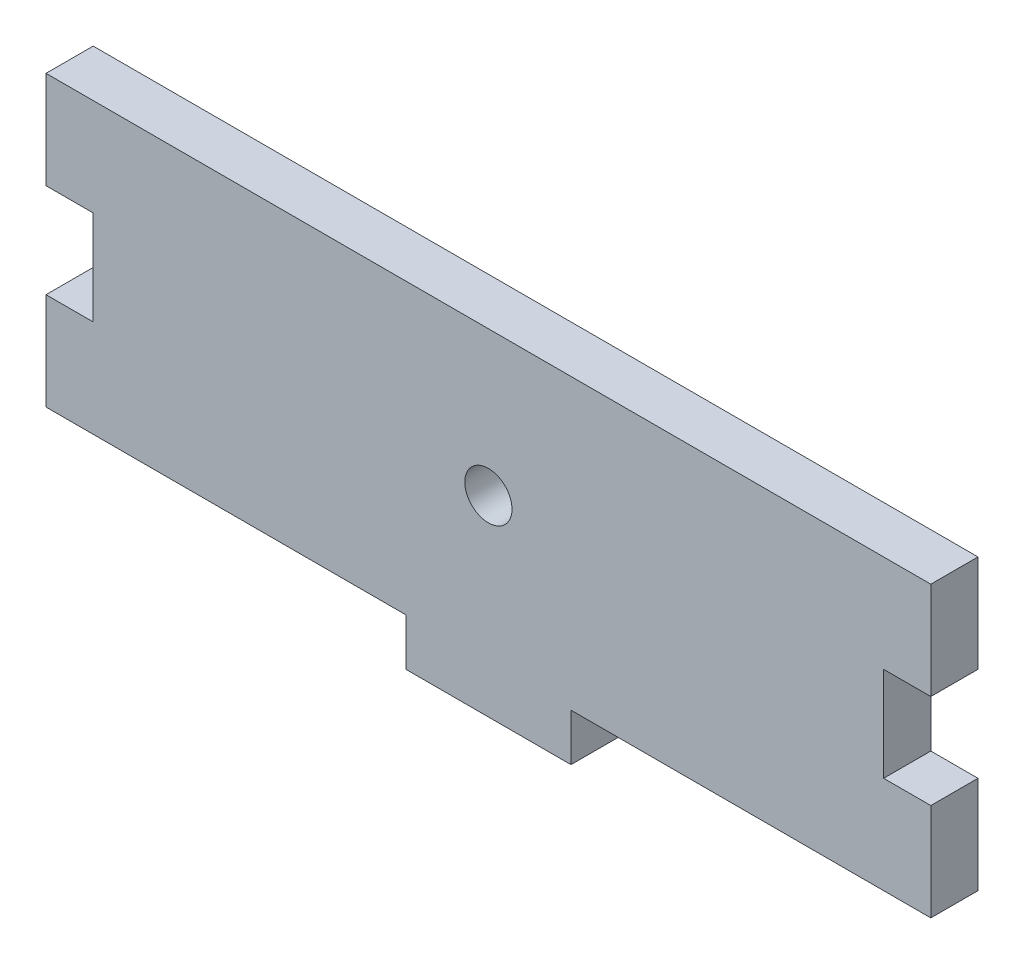
SolidWorks part; units mm, degrees
ref_plane "Alzado" through (0, 0, 0) normal (0, 0, 1) x (1, 0, 0)
ref_plane "Planta" through (0, 0, 0) normal (0, 1, 0) x (1, 0, 0)
ref_plane "Vista lateral" through (0, 0, 0) normal (1, 0, 0) x (0, 0, -1)
sketch "Croquis1" plane through (0, 0, 0) normal (0, 0, 1) x (1, 0, 0)
  line L0 (0, 0) -> (4, 0) construction
  line L1 (37.5, 12.25) -> (-37.5, 12.25)
  line L2 (37.5, 12.25) -> (37.5, 4)
  line L3 (37.5, -12.25) -> (7, -12.25)
  line L4 (-37.5, 12.25) -> (-37.5, 4)
  line L5 (37.5, 12.25) -> (-37.5, -12.25) construction
  line L6 (37.5, -12.25) -> (-37.5, 12.25) construction
  line L7 (0, 12.25) -> (0, -12.25) construction
  line L8 (4, 12.25) -> (4, -12.25) construction
  line L9 (-37.5, 4) -> (37.5, 4) construction
  line L10 (0, 0) -> (4, 4) construction
  line L11 (-37.5, 0) -> (37.5, 0) construction
  line L12 (7, 12.25) -> (7, -12.25) construction
  line L13 (-37.5, -4) -> (37.5, -4) construction
  line L14 (7, -12.25) -> (7, -16.25)
  line L15 (7, -16.25) -> (-7, -16.25)
  line L16 (-7, -16.25) -> (-7, -12.25)
  line L17 (-7, -12.25) -> (-37.5, -12.25)
  line L18 (37.5, 4) -> (33.5, 4)
  line L19 (33.5, 4) -> (33.5, -4)
  line L20 (33.5, -4) -> (37.5, -4)
  line L21 (37.5, -4) -> (37.5, -12.25)
  line L22 (-37.5, 4) -> (-33.5, 4)
  line L23 (-33.5, 4) -> (-33.5, -4)
  line L24 (-33.5, -4) -> (-37.5, -4)
  line L25 (-37.5, -4) -> (-37.5, -12.25)
  circle A0 centre (0, 0) radius 2
  point P0 (0, 0)
  dimension "D1" = 7
  dimension "D3" = 14
  dimension "D2" = 8
  dimension "D4" = 8.25
  dimension "D5" = 8.25
extrude "Saliente-Extruir1" add sketch "Croquis1" along normal blind 4
